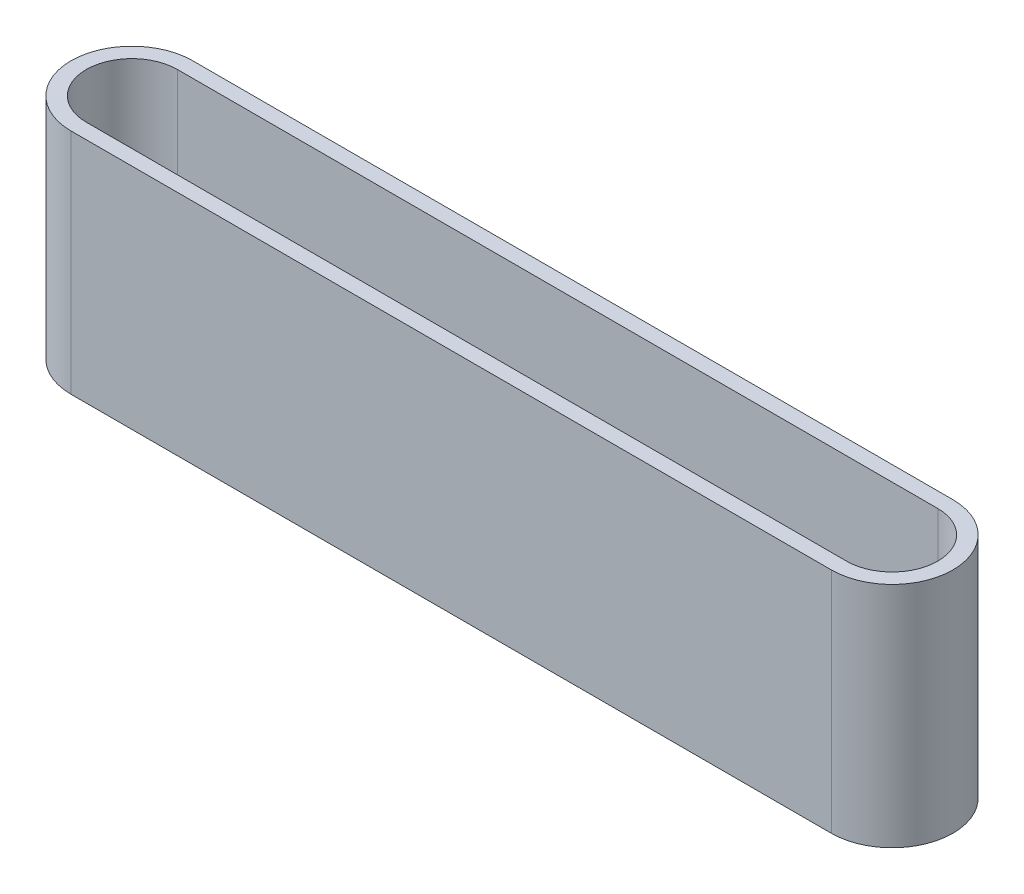
SolidWorks part; units mm, degrees
ref_plane "Front Plane" through (0, 0, 0) normal (0, 0, 1) x (1, 0, 0)
ref_plane "Top Plane" through (0, 0, 0) normal (0, 1, 0) x (1, 0, 0)
ref_plane "Right Plane" through (0, 0, 0) normal (1, 0, 0) x (0, 0, -1)
sketch "Sketch1" plane through (0, 0, 0) normal (0, 1, 0) x (1, 0, 0)
  line L0 (0, 0) -> (-500, 0) construction
  line L1 (0, -40) -> (-500, -40)
  line L2 (0, 40) -> (-500, 40)
  line L3 (0, -30) -> (-500, -30)
  line L4 (0, 30) -> (-500, 30)
  arc A0 (0, -40) -> (0, 40) centre (0, 0) ccw
  arc A1 (-500, 40) -> (-500, -40) centre (-500, 0) ccw
  arc A2 (-500, 30) -> (-500, -30) centre (-500, 0) ccw
  arc A3 (0, -30) -> (0, 30) centre (0, 0) ccw
  point P3 (-250, 0)
  dimension "D2" = 40
  dimension "D1" = 500
  dimension "D3" = 10
extrude "Boss-Extrude1" add sketch "Sketch1" along normal blind 150
